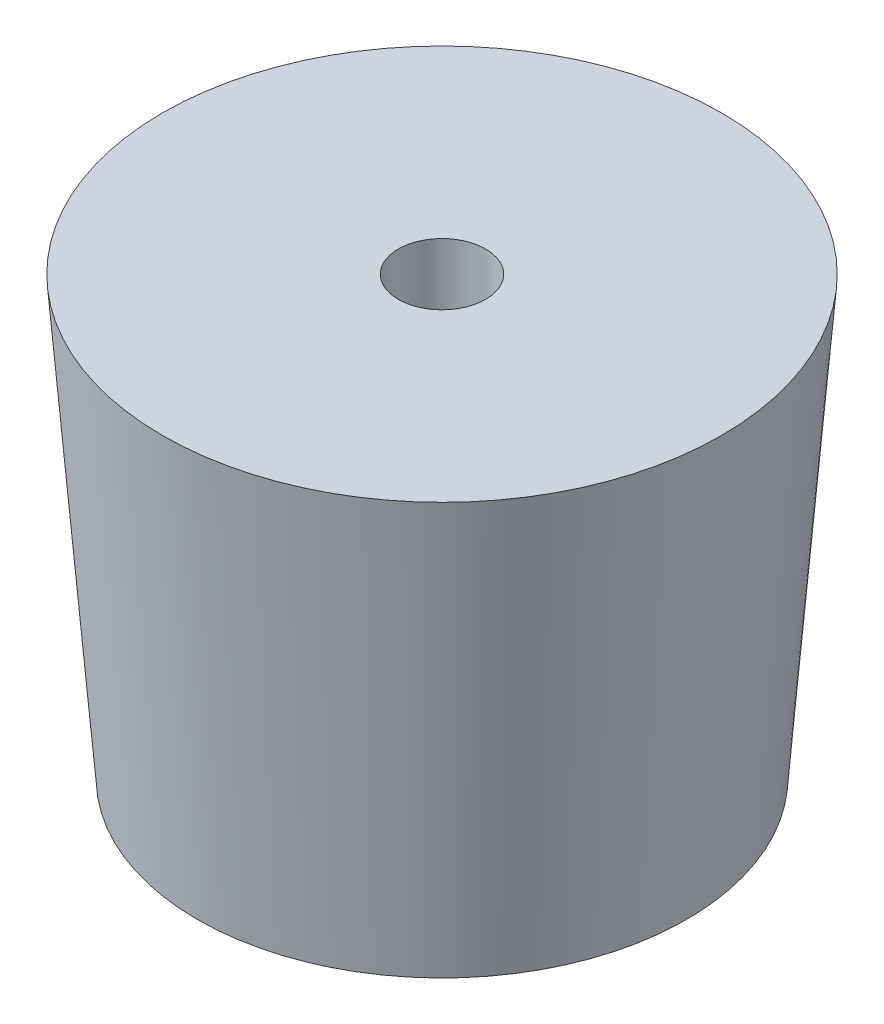
SolidWorks part; units mm, degrees
material "SUS304"
ref_plane "Front Plane" through (0, 0, 0) normal (0, 0, 1) x (1, 0, 0)
ref_plane "Top Plane" through (0, 0, 0) normal (0, 1, 0) x (1, 0, 0)
ref_plane "Right Plane" through (0, 0, 0) normal (1, 0, 0) x (0, 0, -1)
sketch "Sketch1" plane through (0, 0, 0) normal (0, 0, 1) x (1, 0, 0)
  line L0 (0, 0) -> (0, -32.3692) construction
  line L1 (2.5, 0) -> (2.5, -16)
  line L2 (2.5, -16) -> (7, -16)
  line L3 (7, -16) -> (7, -25)
  line L4 (7, -25) -> (14, -25)
  line L5 (14, -25) -> (16, 0)
  line L6 (16, 0) -> (2.5, 0)
  dimension "D1" = 32
  dimension "D2" = 28
  dimension "D3" = 14
  dimension "D4" = 25
  dimension "D5" = 5
  dimension "D6" = 9
revolve "Revolve1" add sketch "Sketch1" angle 360 about L0
equation "\"Mass Kg\"= \"SW-Mass\""
